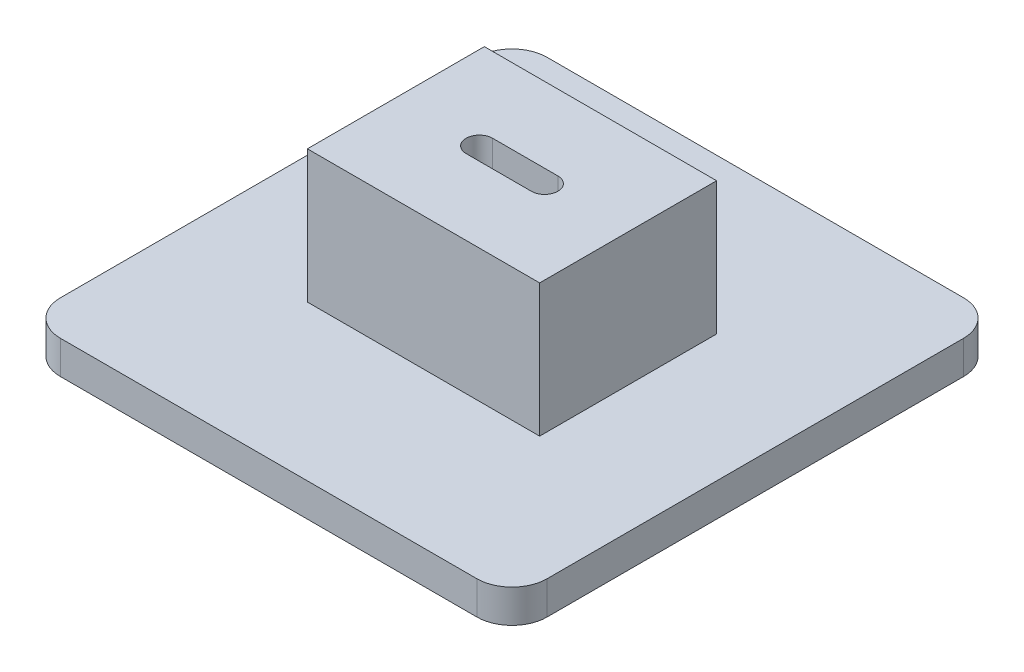
SolidWorks part; units mm, degrees
ref_plane "Front Plane" through (0, 0, 0) normal (0, 0, 1) x (1, 0, 0)
ref_plane "Top Plane" through (0, 0, 0) normal (0, 1, 0) x (1, 0, 0)
ref_plane "Right Plane" through (0, 0, 0) normal (1, 0, 0) x (0, 0, -1)
sketch "Sketch1" plane through (0, 0, 0) normal (0, 1, 0) x (1, 0, 0)
  line L1 (0, 0) -> (44, 0)
  line L2 (0, 0) -> (0, 44)
  line L3 (0, 44) -> (44, 44)
  line L4 (44, 0) -> (44, 44)
  dimension "D1" = 44
extrude "Boss-Extrude1" add sketch "Sketch1" along normal blind 3
sketch "Sketch2" plane through (0, 3, 0) normal (0, 1, 0) x (1, 0, 0)
  line L0 (22, 30) -> (22, 44) construction
  line L1 (11.5, 30) -> (32.5, 30)
  line L2 (11.5, 30) -> (11.5, 14)
  line L3 (11.5, 14) -> (32.5, 14)
  line L4 (32.5, 30) -> (32.5, 14)
  line L5 (44, 44) -> (0, 44) construction
  line L6 (32.5, 22) -> (44, 22) construction
  line L7 (44, 0) -> (44, 44) construction
  dimension "D1" = 21
  dimension "D2" = 16
extrude "Boss-Extrude2" add sketch "Sketch2" along normal blind 12
sketch "Sketch3" plane through (0, 0, 0) normal (0, -1, 0) x (1, 0, 0)
  line L0 (22, -17) -> (22, -14) construction
  line L1 (14.5, -17) -> (29.5, -17)
  line L2 (14.5, -17) -> (14.5, -27)
  line L3 (14.5, -27) -> (29.5, -27)
  line L4 (29.5, -17) -> (29.5, -27)
  line L5 (11.5, -14) -> (32.5, -14) construction
  line L6 (29.5, -22) -> (32.5, -22) construction
  line L7 (32.5, -14) -> (32.5, -30) construction
  dimension "D1" = 15
  dimension "D2" = 10
extrude "Cut-Extrude1" cut sketch "Sketch3" against normal blind 12
sketch "Sketch4" plane through (0, 15, 0) normal (0, 1, 0) x (1, 0, 0)
  line L0 (19.05, 22) -> (24.95, 22) construction
  line L1 (19.05, 23.2) -> (24.95, 23.2)
  line L2 (19.05, 20.8) -> (24.95, 20.8)
  line L3 (22, 22) -> (22, 14) construction
  line L4 (11.5, 14) -> (32.5, 14) construction
  line L5 (24.95, 22) -> (32.5, 22) construction
  line L6 (32.5, 14) -> (32.5, 30) construction
  arc A0 (19.05, 23.2) -> (19.05, 20.8) centre (19.05, 22) ccw
  arc A1 (24.95, 20.8) -> (24.95, 23.2) centre (24.95, 22) ccw
  point P2 (22, 22)
  dimension "D1" = 2.4
  dimension "D2" = 5.9
extrude "Cut-Extrude2" cut sketch "Sketch4" against normal up to next
fillet "Fillet1" radius 3.175 4 edges at (44, 1.5, -44) (44, 1.5, 0) (0, 1.5, 0) (0, 1.5, -44)
